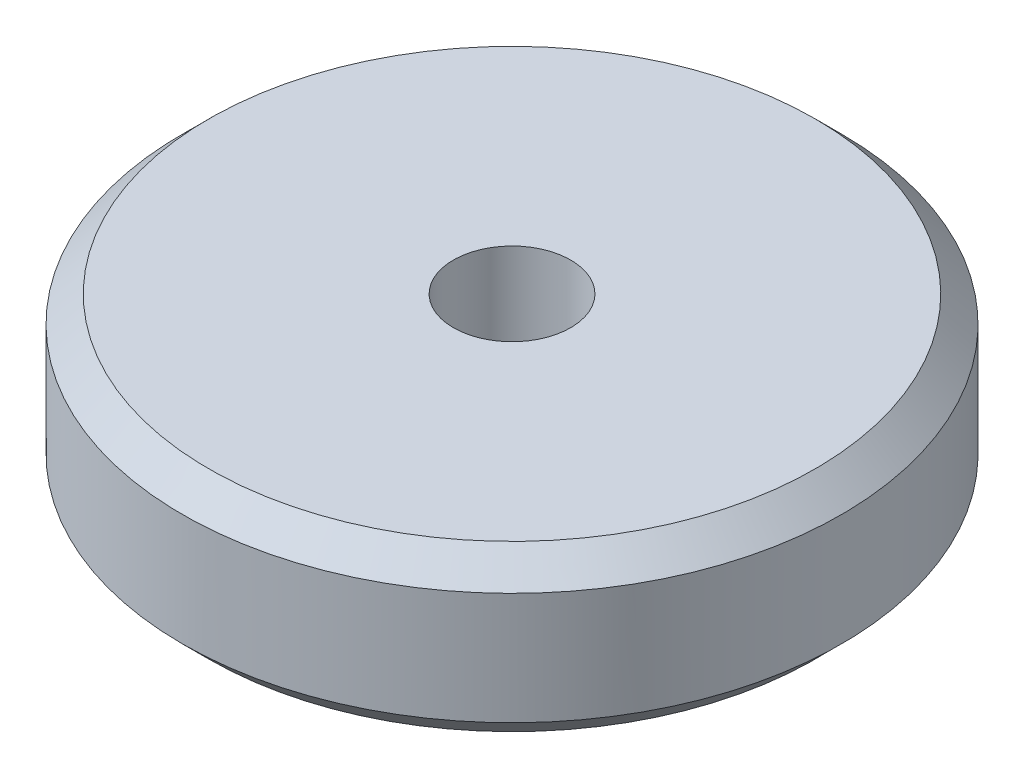
SolidWorks part; units mm, degrees
material "Brass"
ref_plane "Front Plane" through (0, 0, 0) normal (0, 0, 1) x (1, 0, 0)
ref_plane "Top Plane" through (0, 0, 0) normal (0, 1, 0) x (1, 0, 0)
ref_plane "Right Plane" through (0, 0, 0) normal (1, 0, 0) x (0, 0, -1)
sketch "Sketch1" plane through (0, 0, 0) normal (0, 1, 0) x (1, 0, 0)
  circle A0 centre (0, 0) radius 6.35
  dimension "D1" = 12.7
extrude "Boss-Extrude1" add sketch "Sketch1" along normal blind 3.175
hole_wizard "#4-40 Tapped Hole1" positions "Sketch2" profile "Sketch3" tap size "#4-40" standard "ANSI Inch" end condition through all
sketch "Sketch2" plane through (0, 3.175, 0) normal (0, 1, 0) x (1, 0, 0)
  point P0 (0, 0)
sketch "Sketch3" plane through (0, 3.175, 0) normal (1, 0, 0) x (0, 0, 1)
  line L0 (0, 0) -> (0, 3.175)
  line L1 (0, 3.175) -> (1.1303, 3.175)
  line L2 (1.1303, 3.175) -> (1.1303, 0)
  line L5 (1.1303, 0) -> (0, 0)
  line L11 (0, -6.35) -> (0, 107.95) construction
  dimension "Thru Tap Drill Dia." = 2.2606
  dimension "Thru Tap Drill Depth" = 3.175
cosmetic thread "Hole Thread1" parameters "D2"=2.8448
chamfer "Chamfer1" distance 0.508 angle 45 2 edges at (0, 0, 6.35) (0, 3.175, 6.35)
